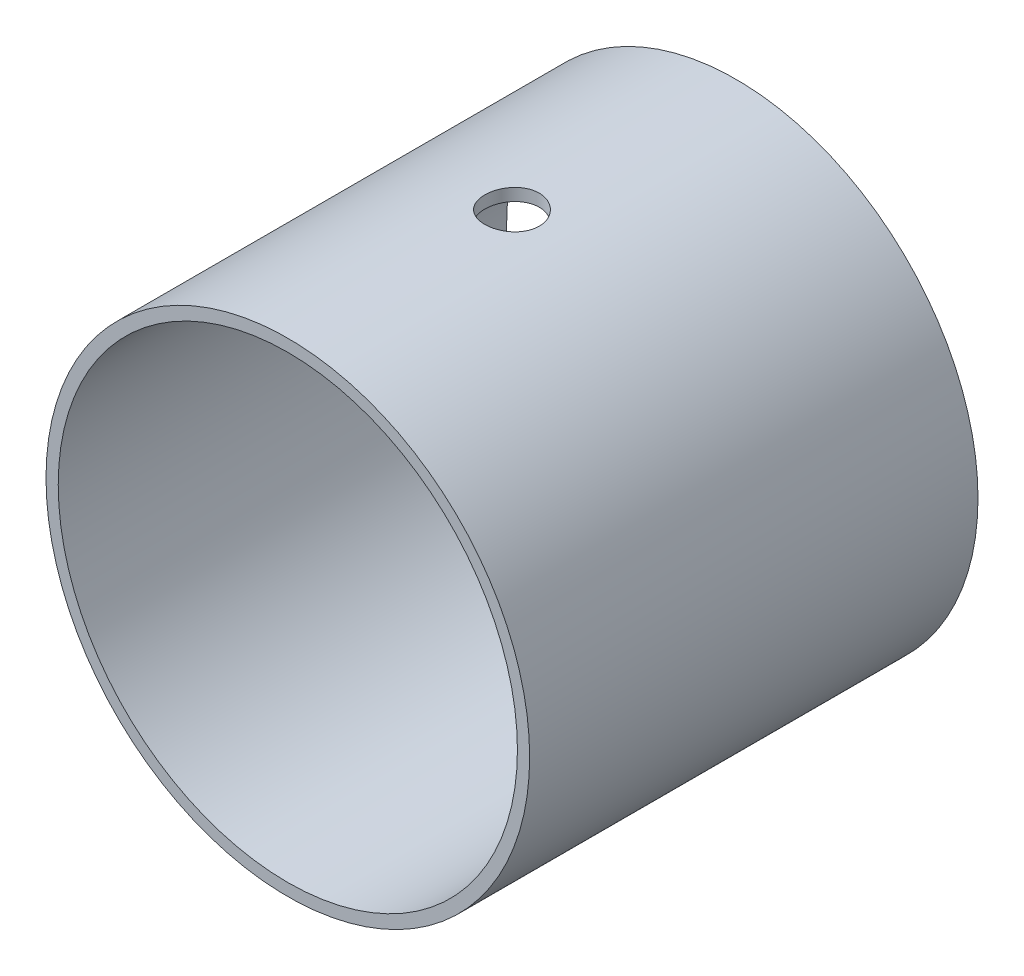
SolidWorks part; units mm, degrees
ref_plane "Alzado" through (0, 0, 0) normal (0, 0, 1) x (1, 0, 0)
ref_plane "Planta" through (0, 0, 0) normal (0, 1, 0) x (1, 0, 0)
ref_plane "Vista lateral" through (0, 0, 0) normal (1, 0, 0) x (0, 0, -1)
sketch "Croquis1" plane through (0, 0, 0) normal (0, 0, 1) x (1, 0, 0)
  circle A0 centre (0, 0) radius 16.9
  circle A1 centre (0, 0) radius 17.8
  dimension "D1" = 35.6
  dimension "D2" = 33.8
extrude "Saliente-Extruir1" add sketch "Croquis1" along normal mid plane 33
ref_plane "Plano1" through (0, 17.8, 0) normal (0, 1, 0) x (-1, 0, 0)
sketch "Croquis2" plane through (0, 17.8, 0) normal (0, 1, 0) x (-1, 0, 0)
  circle A0 centre (0, 0) radius 2
  dimension "D1" = 4
extrude "Cortar-Extruir1" cut sketch "Croquis2" against normal blind 26
